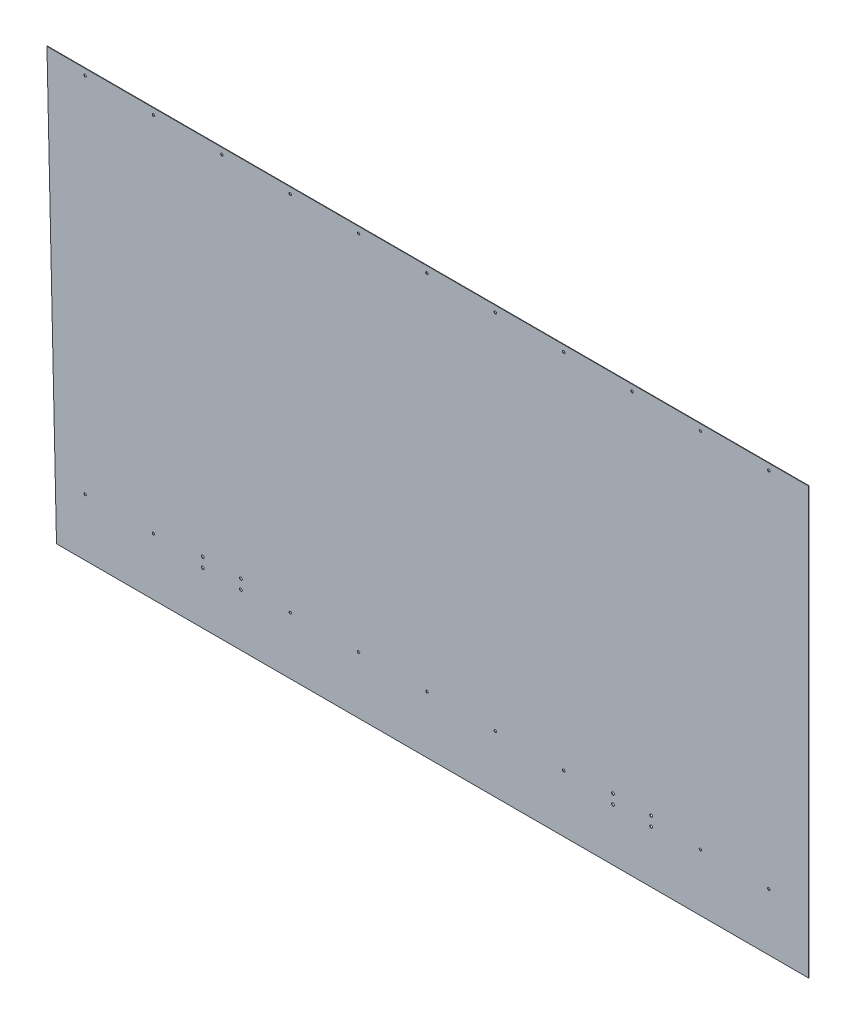
SolidWorks part; units mm, degrees
ref_plane "front" through (0, 0, 0) normal (0, 0, 1) x (1, 0, 0)
ref_plane "top" through (0, 0, 0) normal (0, 1, 0) x (1, 0, 0)
ref_plane "right" through (0, 0, 0) normal (1, 0, 0) x (0, 0, -1)
sketch "Sketch1" plane through (0, 0, 0) normal (0, 0, 1) x (1, 0, 0)
  line L0 (0, 0) -> (1501.775, 0)
  line L1 (1501.775, 0) -> (1501.775, 850.9)
  line L2 (1501.775, 850.9) -> (-19.05, 850.9)
  line L3 (-19.05, 850.9) -> (0, 0)
  line L4 (57.15, 114.3) -> (1422.4, 114.3) construction
  line L5 (57.15, 838.2) -> (1422.4, 838.2) construction
  line L6 (1473.2, 0) -> (1473.2, 850.9) construction
  circle A0 centre (57.15, 114.3) radius 2.3876
  circle A1 centre (292.1, 104.775) radius 2.7813
  circle A2 centre (292.1, 123.825) radius 2.7813
  circle A3 centre (193.675, 114.3) radius 2.3876
  circle A4 centre (466.725, 114.3) radius 2.3876
  circle A5 centre (603.25, 114.3) radius 2.3876
  circle A6 centre (739.775, 114.3) radius 2.3876
  circle A7 centre (1111.25, 123.825) radius 2.7813
  circle A8 centre (1111.25, 104.775) radius 2.7813
  circle A9 centre (1422.4, 114.3) radius 2.3876
  circle A10 centre (368.3, 104.775) radius 2.7813
  circle A11 centre (368.3, 123.825) radius 2.7813
  circle A12 centre (876.3, 114.3) radius 2.3876
  circle A13 centre (1285.875, 114.3) radius 2.3876
  circle A14 centre (1187.45, 123.825) radius 2.7813
  circle A15 centre (1187.45, 104.775) radius 2.7813
  circle A16 centre (1012.825, 114.3) radius 2.3876
  circle A17 centre (57.15, 838.2) radius 2.4257
  circle A18 centre (193.675, 838.2) radius 2.4257
  circle A19 centre (330.2, 838.2) radius 2.4257
  circle A20 centre (466.725, 838.2) radius 2.4257
  circle A21 centre (603.25, 838.2) radius 2.4257
  circle A22 centre (739.775, 838.2) radius 2.4257
  circle A23 centre (876.3, 838.2) radius 2.4257
  circle A24 centre (1012.825, 838.2) radius 2.4257
  circle A25 centre (1149.35, 838.2) radius 2.4257
  circle A26 centre (1285.875, 838.2) radius 2.4257
  circle A27 centre (1422.4, 838.2) radius 2.4257
  dimension "D7" = 5.5626
  dimension "D17" = 4.7752
  dimension "D14" = 4.8514
  dimension "D1" = 9.525
  dimension "D2" = 850.9
  dimension "D3" = 1501.775
  dimension "D4" = 19.05
  dimension "D5" = 9.525
  dimension "D8" = 9.525
  dimension "D9" = 9.525
  dimension "D10" = 57.15
  dimension "D11" = 50.8
  dimension "D15" = 76.2
  dimension "D16" = 114.3
  dimension "D18" = 76.2
  dimension "D19" = 12.7
  dimension "D20" = 57.15
  dimension "D22" = 79.375
  dimension "D23" = 1492.25
  dimension "D24" = 1473.2
extrude "Extrude1" add sketch "Sketch1" against normal blind 1.016
